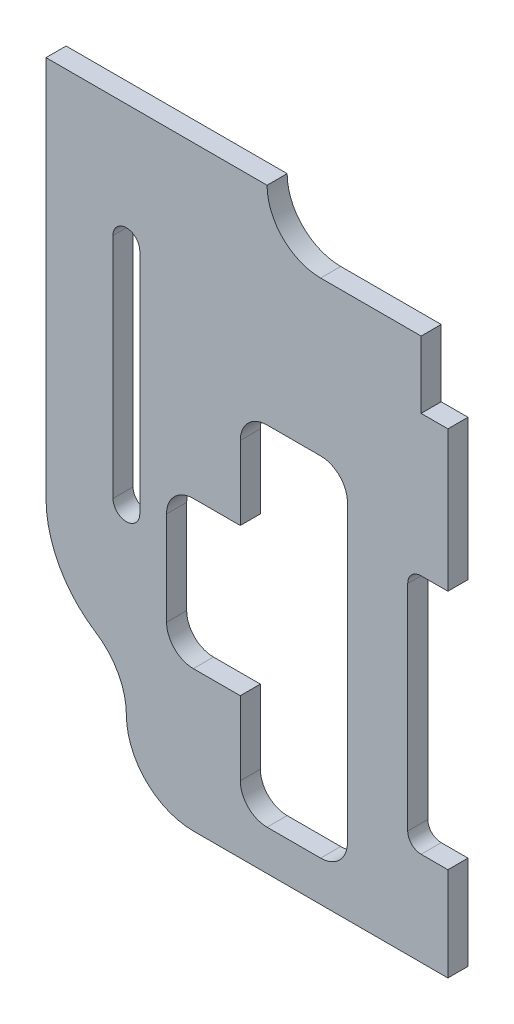
SolidWorks part; units mm, degrees
ref_plane "Front Plane" through (0, 0, 0) normal (0, 0, 1) x (1, 0, 0)
ref_plane "Top Plane" through (0, 0, 0) normal (0, 1, 0) x (1, 0, 0)
ref_plane "Right Plane" through (0, 0, 0) normal (1, 0, 0) x (0, 0, -1)
sketch "Sketch1" plane through (0, 0, 0) normal (0, 0, 1) x (1, 0, 0)
  line L0 (-19, 0) -> (0, 0)
  line L1 (0, 0) -> (0, 7)
  line L3 (-3, 8) -> (-3, 24)
  line L4 (-2, 25) -> (0, 25)
  line L8 (-2, 40.5) -> (-9.5, 40.5)
  line L9 (-13.5, 44.5) -> (-30, 44.5)
  line L10 (-30, 44.5) -> (-30, 16)
  line L13 (0, 7) -> (-2, 7)
  line L14 (-2, 40.5) -> (-2, 35.5)
  line L15 (-2, 35.5) -> (0, 35.5)
  line L16 (0, 35.5) -> (0, 25)
  line L17 (-25, 35.5) -> (-25, 18.5)
  line L18 (-23, 18.5) -> (-23, 35.5)
  line L19 (-7.5, 5) -> (-7.5, 27)
  line L20 (-9.5, 29) -> (-13.5, 29)
  line L21 (-15.5, 27) -> (-15.5, 21.5)
  line L22 (-15.5, 21.5) -> (-19, 21.5)
  line L23 (-21, 19.5) -> (-21, 12.5)
  line L24 (-19, 10.5) -> (-15.5, 10.5)
  line L25 (-15.5, 10.5) -> (-15.5, 5)
  line L26 (-9.5, 3) -> (-13.5, 3)
  arc A0 (-2, 7) -> (-3, 8) centre (-2, 8) cw
  arc A1 (-3, 24) -> (-2, 25) centre (-2, 24) cw
  arc A3 (-9.5, 40.5) -> (-13.5, 44.5) centre (-9.5, 44.5) cw
  arc A5 (-26.293, 9.2038) -> (-24, 5) centre (-29, 5) cw
  arc A6 (-24, 5) -> (-19, 0) centre (-19, 5) ccw
  arc A7 (-30, 16) -> (-26.293, 9.2038) centre (-21.9167, 16) ccw
  arc A8 (-25, 18.5) -> (-23, 18.5) centre (-24, 18.5) ccw
  arc A9 (-23, 35.5) -> (-25, 35.5) centre (-24, 35.5) ccw
  arc A10 (-7.5, 27) -> (-9.5, 29) centre (-9.5, 27) ccw
  arc A11 (-13.5, 29) -> (-15.5, 27) centre (-13.5, 27) ccw
  arc A12 (-19, 21.5) -> (-21, 19.5) centre (-19, 19.5) ccw
  arc A13 (-21, 12.5) -> (-19, 10.5) centre (-19, 12.5) ccw
  arc A14 (-15.5, 5) -> (-13.5, 3) centre (-13.5, 5) ccw
  arc A15 (-7.5, 5) -> (-9.5, 3) centre (-9.5, 5) cw
  point P4 (-3, 16)
  point P51 (0, 0)
  point P52 (0, 0)
  point P53 (0, 0)
  point P54 (0, 0)
  point P55 (0, 0)
  point P56 (0, 0)
  point P57 (0, 0)
  point P58 (0, 0)
  point P59 (0, 0)
  dimension "D1" = 5
  dimension "D2" = 5
  dimension "D4" = 1
  dimension "D5" = 1
  dimension "D17" = 2
  dimension "D9" = 2
  dimension "D22" = 1
  dimension "D24" = 28
  dimension "D3" = 4
  dimension "D6" = 30
  dimension "D7" = 19
  dimension "D8" = 16.5
  dimension "D10" = 44.5
  dimension "D11" = 24
  dimension "D12" = 9.5
  dimension "D13" = 32.5
  dimension "D14" = 2
  dimension "D15" = 5
  dimension "D16" = 2
  dimension "D18" = 35.5
  dimension "D19" = 13.5
  dimension "D20" = 22
  dimension "D21" = 5
  dimension "D23" = 13.5
  dimension "D25" = 21
extrude "Boss-Extrude1" add sketch "Sketch1" along normal blind 1.5
sketch "Sketch2" plane through (0, 0, 0) normal (0, 0, 1) x (1, 0, 0)
  line L0 (-30, 44.5) -> (-30, 16) construction
  line L3 (-30, 30.25) -> (-25, 30.25) construction
  line L4 (-25, 35.5) -> (-25, 18.5) construction
  line L6 (-27.5, 50.696) -> (-27.5, 3.0227) construction
